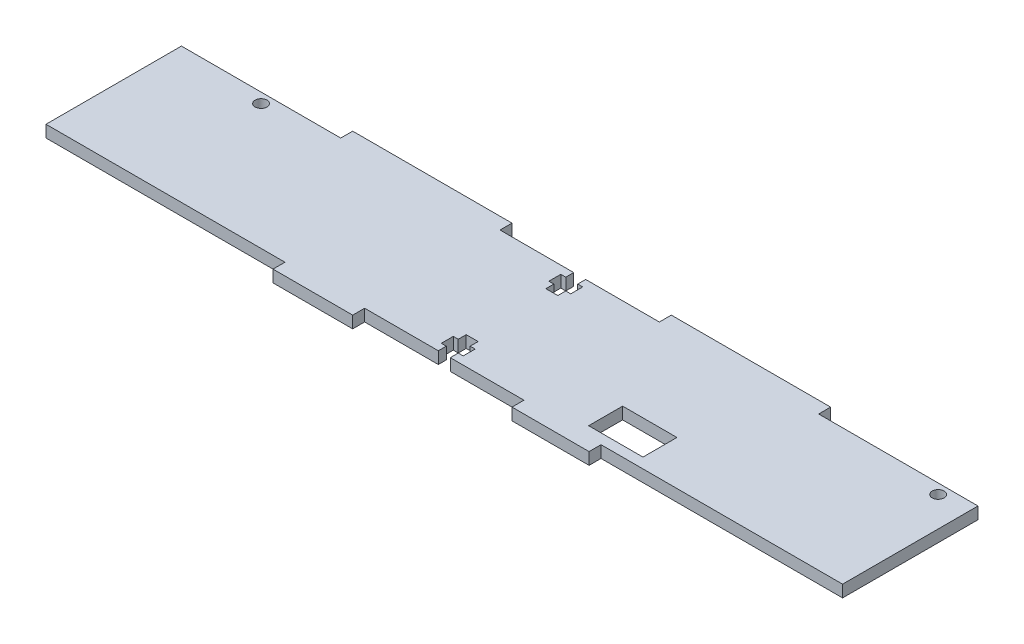
SolidWorks part; units mm, degrees
ref_plane "Front Plane" through (0, 0, 0) normal (0, 0, 1) x (1, 0, 0)
ref_plane "Top Plane" through (0, 0, 0) normal (0, 1, 0) x (1, 0, 0)
ref_plane "Right Plane" through (0, 0, 0) normal (1, 0, 0) x (0, 0, -1)
sketch "Sketch1" plane through (0, 0, 0) normal (0, 1, 0) x (1, 0, 0)
  line L0 (0, 20) -> (0, -20) construction
  line L1 (-100, -20) -> (100, -20)
  line L2 (-100, -20) -> (-100, 20)
  line L3 (-100, 20) -> (100, 20)
  line L4 (100, -20) -> (100, 20)
  line L5 (-100, -20) -> (100, 20) construction
  line L6 (-100, 20) -> (100, -20) construction
  line L7 (-100, 0) -> (100, 0) construction
  point P0 (0, 0)
  dimension "D1" = 40
  dimension "D2" = 200
extrude "Boss-Extrude1" add sketch "Sketch1" along normal blind 3
sketch "Sketch3" plane through (0, 3, 0) normal (0, 1, 0) x (1, 0, 0)
  line L0 (0, -20) -> (0, 20) construction
  line L1 (100, 20) -> (-100, 20) construction
  line L2 (-100, -20) -> (100, -20) construction
  line L3 (-100, 0) -> (100, 0) construction
  line L4 (-100, 20) -> (-100, -20) construction
  line L5 (100, -20) -> (100, 20) construction
  line L14 (-20, -20) -> (-20, -17)
  line L15 (-20, -17) -> (-1.5, -17)
  line L16 (-1.5, -17) -> (-1.5, -15)
  line L17 (-1.5, -15) -> (-2.75, -15)
  line L18 (-2.75, -15) -> (-2.75, -12)
  line L19 (-2.75, -12) -> (-1.5, -12)
  line L20 (-1.5, -12) -> (-1.5, -10)
  line L21 (-1.5, -10) -> (1.5, -10)
  line L22 (-20, -20) -> (20, -20)
  line L23 (1.5, -12) -> (1.5, -10)
  line L24 (2.75, -12) -> (1.5, -12)
  line L25 (2.75, -15) -> (2.75, -12)
  line L26 (1.5, -15) -> (2.75, -15)
  line L27 (1.5, -17) -> (1.5, -15)
  line L28 (20, -17) -> (1.5, -17)
  line L29 (20, -20) -> (20, -17)
  line L30 (-40, -20) -> (-40, -17)
  line L31 (-40, -17) -> (-100, -17)
  line L32 (-100, -17) -> (-100, -20)
  line L33 (-100, -20) -> (-40, -20)
  line L34 (100, -17) -> (100, -20)
  line L35 (39.3506, -17) -> (100, -17)
  line L36 (39.3506, -20) -> (39.3506, -17)
  line L37 (100, -20) -> (39.3506, -20)
  line L85 (85, 17) -> (100, 17)
  line L86 (100, 17) -> (100, 20)
  line L87 (100, 20) -> (60, 20)
  line L88 (60, 20) -> (60, 17)
  line L89 (60, 17) -> (82, 17)
  line L101 (20, 20) -> (20, 17)
  line L102 (20, 17) -> (1.5, 17)
  line L103 (1.5, 17) -> (1.5, 15)
  line L104 (1.5, 15) -> (2.75, 15)
  line L105 (2.75, 15) -> (2.75, 12)
  line L106 (2.75, 12) -> (1.5, 12)
  line L107 (1.5, 12) -> (1.5, 10)
  line L108 (-20, 20) -> (20, 20)
  line L109 (-1.5, 10) -> (1.5, 10)
  line L110 (-1.5, 12) -> (-1.5, 10)
  line L111 (-2.75, 12) -> (-1.5, 12)
  line L112 (-2.75, 15) -> (-2.75, 12)
  line L113 (-1.5, 15) -> (-2.75, 15)
  line L114 (-1.5, 17) -> (-1.5, 15)
  line L115 (-20, 17) -> (-1.5, 17)
  line L116 (-20, 20) -> (-20, 17)
  line L117 (82, 17) -> (85, 17)
  line L118 (-60, 20) -> (-60, 17)
  line L119 (-100, 20) -> (-60, 20)
  line L120 (-100, 17) -> (-100, 20)
  line L121 (-85, 17) -> (-100, 17)
  line L122 (-82, 17) -> (-85, 17)
  line L123 (-60, 17) -> (-82, 17)
  point P17 (0, -17)
  point P23 (0, -10)
  point P90 (0, 10)
  point P91 (0, 17)
  dimension "D2" = 3
  dimension "D3" = 3
  dimension "D4" = 3
  dimension "D5" = 3
  dimension "D6" = 2
  dimension "D7" = 3
  dimension "D8" = 2
  dimension "D9" = 3
  dimension "D10" = 5.5
  dimension "D12" = 3
extrude "Cut-Extrude1" cut sketch "Sketch3" against normal blind 3
sketch "Sketch4" plane through (0, 3, 0) normal (0, 1, 0) x (1, 0, 0)
  line L1 (47.3126, -5.9013) -> (33.6726, -5.9013)
  line L2 (47.3126, -5.9013) -> (47.3126, -14.4313)
  line L3 (47.3126, -14.4313) -> (33.6726, -14.4313)
  line L4 (33.6726, -5.9013) -> (33.6726, -14.4313)
  dimension "D1" = 13.64
  dimension "D2" = 8.53
extrude "Cut-Extrude2" cut sketch "Sketch4" against normal blind 3
sketch "Sketch6" plane through (0, 0, 0) normal (0, -1, 0) x (1, 0, 0)
  circle A0 centre (92.5, -14.5) radius 1.5
  circle A1 centre (-77.5, -14.5) radius 1.5
extrude "Cut-Extrude3" cut sketch "Sketch6" against normal blind 3
